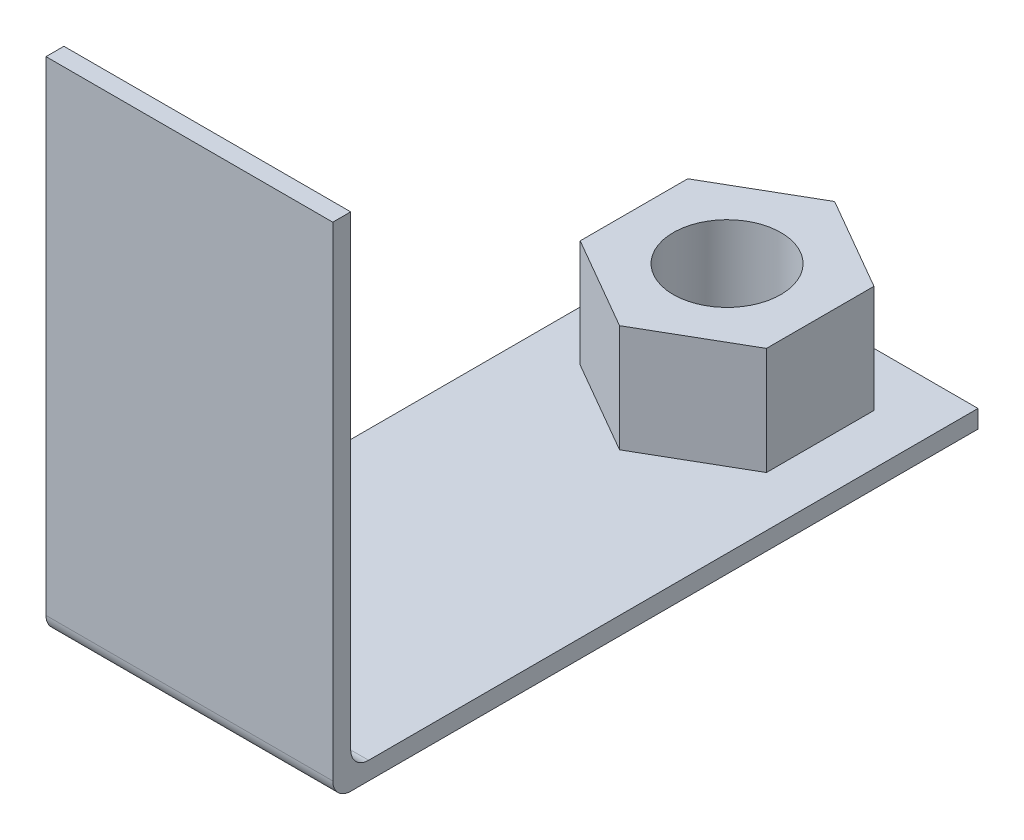
SolidWorks part; units mm, degrees
material "AISI 304"
ref_plane "Front Plane" through (0, 0, 0) normal (0, 0, 1) x (1, 0, 0)
ref_plane "Top Plane" through (0, 0, 0) normal (0, 1, 0) x (1, 0, 0)
ref_plane "Right Plane" through (0, 0, 0) normal (1, 0, 0) x (0, 0, -1)
sketch "Sketch1" plane through (0, 0, 0) normal (0, 1, 0) x (1, 0, 0)
  line L0 (0, 0) -> (-4, 0)
  line L1 (0, 0) -> (4, 0)
  line L2 (-4, 0) -> (-4, 18)
  line L3 (-4, 18) -> (4, 18)
  line L4 (4, 18) -> (4, 0)
extrude "Boss-Extrude1" add sketch "Sketch1" along normal blind 0.5
sketch "Sketch2" plane through (0, 0, 0) normal (0, 1, 0) x (1, 0, 0)
  line L0 (-4, 0) -> (-4, 0.5)
  line L1 (-4, 18) -> (-4, 0) construction
  line L2 (-4, 0) -> (4, 0)
  line L3 (4, 0) -> (4, 0.5)
  line L4 (4, 0) -> (4, 18) construction
  line L5 (4, 0.5) -> (-4, 0.5)
extrude "Boss-Extrude2" add sketch "Sketch2" along normal blind 14
sketch "Sketch3" plane through (0, 0.5, 0) normal (0, 1, 0) x (1, 0, 0)
  line L1 (0, 18) -> (-2.5981, 16.5)
  line L2 (-2.5981, 16.5) -> (-2.5981, 13.5)
  line L3 (-2.5981, 13.5) -> (0, 12)
  line L4 (0, 12) -> (2.5981, 13.5)
  line L5 (2.5981, 13.5) -> (2.5981, 16.5)
  line L6 (2.5981, 16.5) -> (0, 18)
  circle A0 centre (0, 15) radius 2.5981 construction
  point P0 (0, 15)
extrude "Boss-Extrude3" add sketch "Sketch3" along normal blind 3
sketch "Sketch4" plane through (0, 3.5, 0) normal (0, 1, 0) x (1, 0, 0)
  circle A0 centre (0, 15) radius 1.5
extrude "Cut-Extrude1" cut sketch "Sketch4" against normal blind 13
fillet "Fillet1" radius 0.5 1 edges at (0, 0, 0)
fillet "Fillet2" radius 0.5 1 edges at (0, 0.5, -0.5)
sketch "Sketch5" plane through (0, 0, -0.5) normal (0, 0, -1) x (-1, 0, 0)
  circle A0 centre (0, 10.3413) radius 2.8384
extrude "Boss-Extrude4" add sketch "Sketch5" along normal blind 0.3
